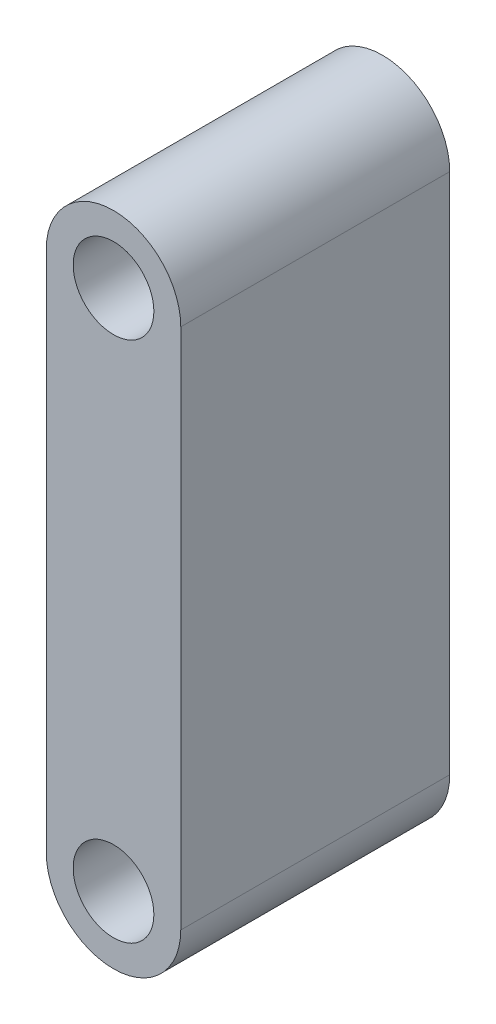
SolidWorks part; units mm, degrees
ref_plane "Piano frontale" through (0, 0, 0) normal (0, 0, 1) x (1, 0, 0)
ref_plane "Piano superiore" through (0, 0, 0) normal (0, 1, 0) x (1, 0, 0)
ref_plane "Piano destro" through (0, 0, 0) normal (1, 0, 0) x (0, 0, -1)
sketch "Schizzo2" plane through (0, 0, 0) normal (0, 0, 1) x (1, 0, 0)
  line L0 (0, 154.5564) -> (0, -39.6436) construction
  line L1 (25, 154.5564) -> (25, -39.6436)
  line L2 (-25, 154.5564) -> (-25, -39.6436)
  arc A0 (25, 154.5564) -> (-25, 154.5564) centre (0, 154.5564) ccw
  arc A1 (-25, -39.6436) -> (25, -39.6436) centre (0, -39.6436) ccw
  circle A2 centre (0, 154.5564) radius 15
  circle A3 centre (0, -39.6436) radius 15
  point P3 (0, 57.4564)
  dimension "D2" = 30
  dimension "D3" = 30
  dimension "D1" = 194.2
  dimension "D4" = 50
extrude "Estrusione-Estrusione1" add sketch "Schizzo2" along normal mid plane 100
